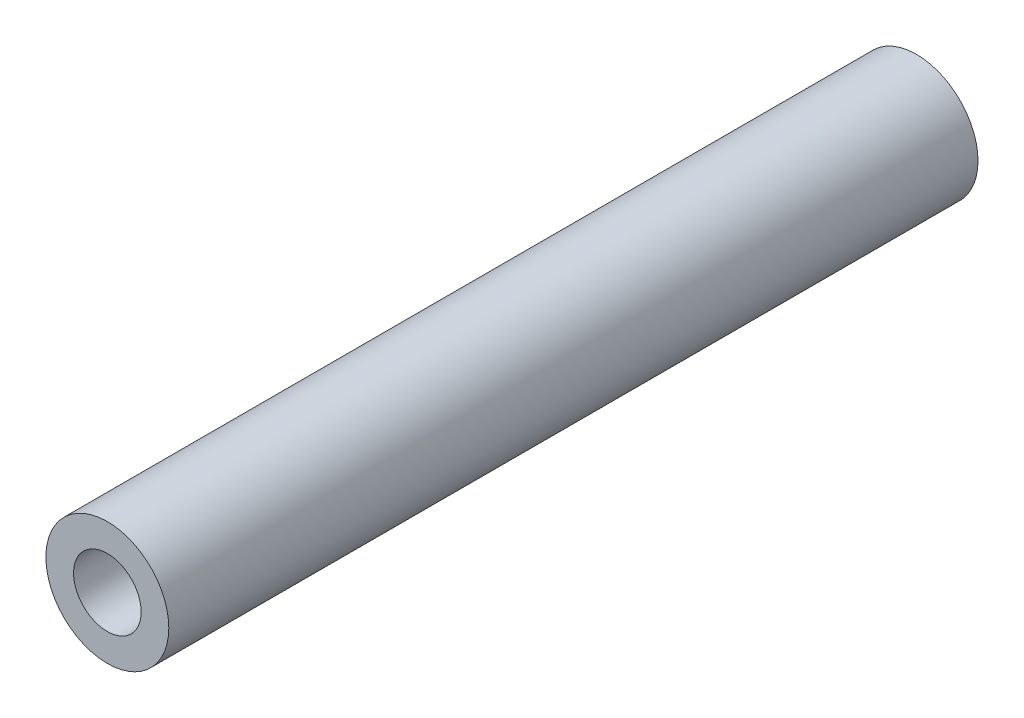
SolidWorks part; units mm, degrees
material "6061 合金"
ref_plane "前视基准面" through (0, 0, 0) normal (0, 0, 1) x (1, 0, 0)
ref_plane "上视基准面" through (0, 0, 0) normal (0, 1, 0) x (1, 0, 0)
ref_plane "右视基准面" through (0, 0, 0) normal (1, 0, 0) x (0, 0, -1)
sketch "草图1" plane through (0, 0, 0) normal (0, 0, 1) x (1, 0, 0)
  circle A1 centre (0, 0) radius 3
  dimension "D1" = 6
extrude "凸台-拉伸1" add sketch "草图1" along normal blind 39.5
hole_wizard "M4 螺纹孔1" positions "草图2" profile "草图3" tap size "M4" standard "GB" end condition through all
sketch "草图2" plane through (0, 0, 39.5) normal (0, 0, 1) x (1, 0, 0)
  point P0 (0, 0)
sketch "草图3" plane through (0, 0, 39.5) normal (1, 0, 0) x (0, -1, 0)
  line L0 (0, 0) -> (0, 39.5)
  line L1 (0, 39.5) -> (1.65, 39.5)
  line L2 (1.65, 39.5) -> (1.65, 0)
  line L5 (1.65, 0) -> (0, 0)
  line L11 (0, -6.35) -> (0, 107.95) construction
  dimension "通孔螺纹孔钻头直径" = 3.3
  dimension "通孔螺纹孔钻头深度" = 39.5
cosmetic thread "孔螺蚊线1" parameters "D2"=4
